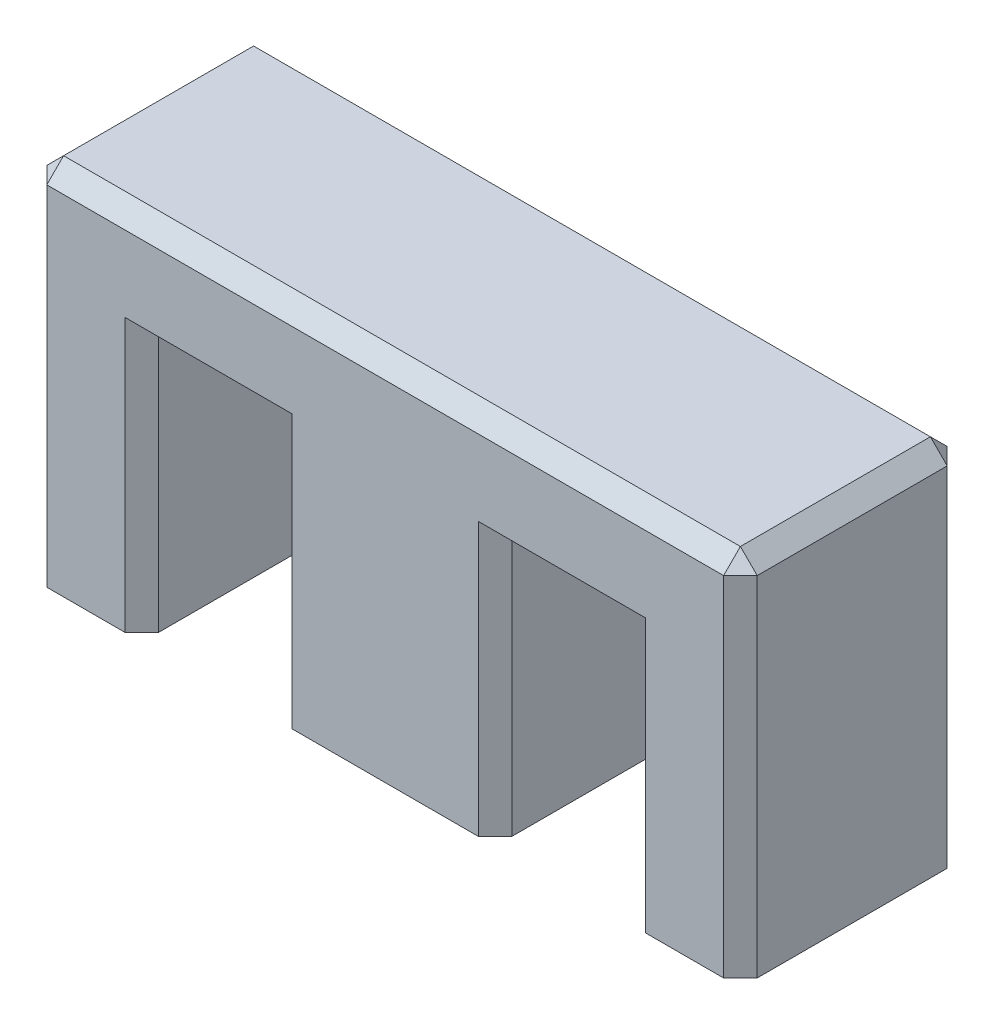
SolidWorks part; units mm, degrees
material "Ductile Iron"
ref_plane "Front Plane" through (0, 0, 0) normal (0, 0, 1) x (1, 0, 0)
ref_plane "Top Plane" through (0, 0, 0) normal (0, 1, 0) x (1, 0, 0)
ref_plane "Right Plane" through (0, 0, 0) normal (1, 0, 0) x (0, 0, -1)
sketch "Sketch1" plane through (0, 0, 0) normal (0, 0, 1) x (1, 0, 0)
  line L0 (0, 33.0544) -> (0, -29.4507) construction
  line L1 (42.25, 31.0235) -> (-42.25, 31.0235)
  line L2 (-42.25, 31.0235) -> (-42.25, -12.4265)
  line L3 (-42.25, -12.4265) -> (-28.95, -12.4265)
  line L4 (-28.95, -12.4265) -> (-28.95, 18.0235)
  line L5 (-28.95, 18.0235) -> (-13.075, 18.0235)
  line L6 (-13.075, 18.0235) -> (-13.075, -12.4265)
  line L7 (-13.075, -12.4265) -> (13.075, -12.4265)
  line L8 (13.075, 18.0235) -> (13.075, -12.4265)
  line L9 (28.95, 18.0235) -> (13.075, 18.0235)
  line L10 (28.95, -12.4265) -> (28.95, 18.0235)
  line L11 (42.25, -12.4265) -> (28.95, -12.4265)
  line L12 (42.25, 31.0235) -> (42.25, -12.4265)
  point P12 (0, -12.4265)
  point P13 (0, 31.0235)
  dimension "D1" = 84.5
  dimension "D2" = 43.45
  dimension "D3" = 26.15
  dimension "D4" = 13
  dimension "D5" = 13.3
extrude "Boss-Extrude1" add sketch "Sketch1" along normal mid plane 26.6
chamfer "Chamfer1" distance 2 angle 45 20 edges at (42.25, 31.0235, 0) (42.25, 9.2985, 13.3) (0, 31.0235, 13.3) (-42.25, 9.2985, 13.3) (-42.25, 31.0235, 0) (-42.25, 9.2985, -13.3) (0, 31.0235, -13.3) (42.25, 9.2985, -13.3) (13.075, 2.7985, -13.3) (28.95, 2.7985, -13.3) (21.0125, 18.0235, -13.3) (-28.95, 2.7985, -13.3) (-13.075, 2.7985, -13.3) (-21.0125, 18.0235, -13.3) (28.95, 2.7985, 13.3) (13.075, 2.7985, 13.3) (21.0125, 18.0235, 13.3) (-28.95, 2.7985, 13.3) (-13.075, 2.7985, 13.3) (-21.0125, 18.0235, 13.3)
